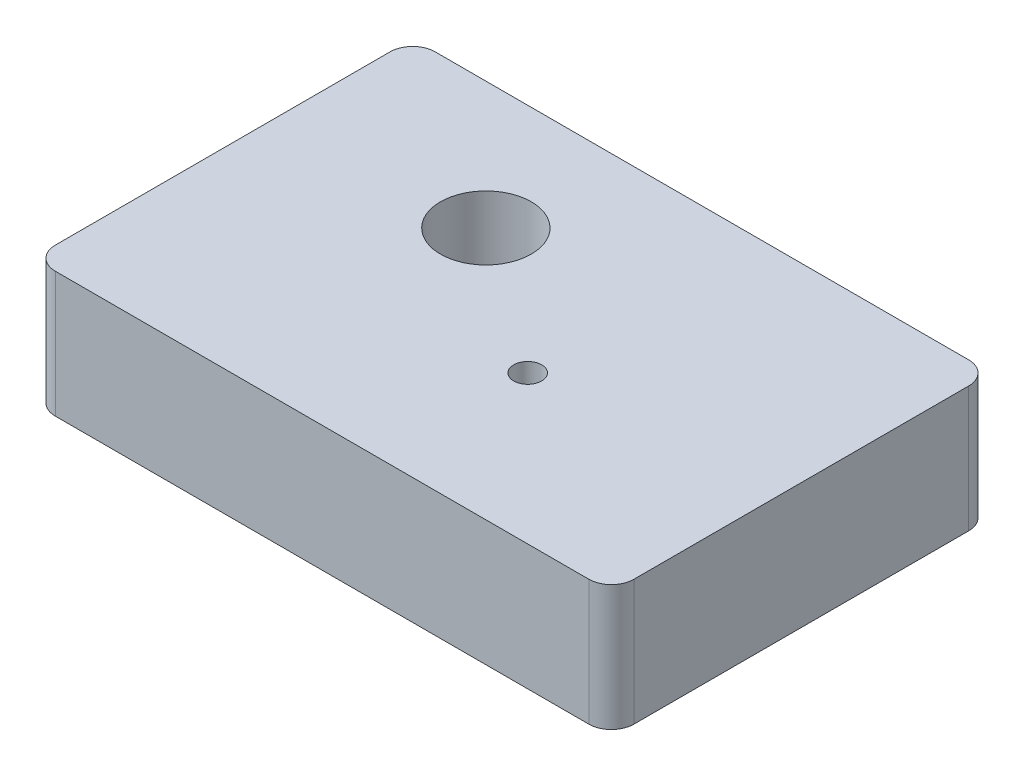
SolidWorks part; units mm, degrees
material "Balsa"
ref_plane "Front Plane" through (0, 0, 0) normal (0, 0, 1) x (1, 0, 0)
ref_plane "Top Plane" through (0, 0, 0) normal (0, 1, 0) x (1, 0, 0)
ref_plane "Right Plane" through (0, 0, 0) normal (1, 0, 0) x (0, 0, -1)
sketch "Sketch1" plane through (0, 0, 0) normal (0, 1, 0) x (1, 0, 0)
  line L1 (0, 0) -> (27.5, 0)
  line L2 (0, 0) -> (0, 18)
  line L3 (0, 18) -> (27.5, 18)
  line L4 (27.5, 0) -> (27.5, 18)
  circle A0 centre (9.5, 12) radius 2.25
  circle A1 centre (16.5, 7) radius 0.75
  dimension "D3" = 1.5
  dimension "D4" = 4.5
  dimension "D1" = 27.5
  dimension "D2" = 18
  dimension "D5" = 9.5
  dimension "D6" = 6
  dimension "D7" = 7
  dimension "D8" = 16.5
extrude "Boss-Extrude1" add sketch "Sketch1" along normal blind 6
fillet "Fillet1" radius 1 4 edges at (0, 3, 0) (0, 3, -18) (27.5, 3, -18) (27.5, 3, 0)
other "Move Face1" face at (16.5, 6, -6.25) face at (9.5, 6, -9.75) face at (0.3964, 3, -0.3964) face at (0, 3, -9) face at (0.3964, 3, -17.6036) face at (13.75, 3, -18) face at (27.1036, 3, -17.6036) face at (27.5, 3, -9) face at (27.1036, 3, -0.3964) face at (13.75, 3, 0) parameters "D1"=0.08
